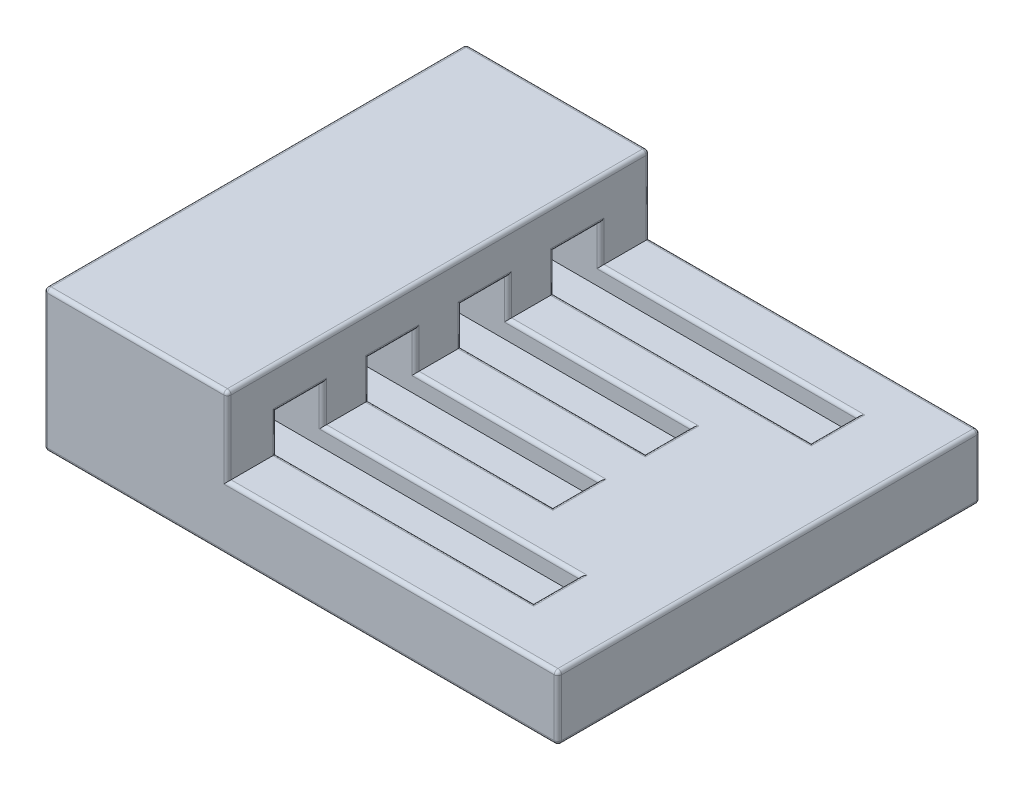
SolidWorks part; units mm, degrees
material "Ceramic Porcelain"
ref_plane "Front Plane" through (0, 0, 0) normal (0, 0, 1) x (1, 0, 0)
ref_plane "Top Plane" through (0, 0, 0) normal (0, 1, 0) x (1, 0, 0)
ref_plane "Right Plane" through (0, 0, 0) normal (1, 0, 0) x (0, 0, -1)
sketch "Sketch1" plane through (0, 0, 0) normal (0, 0, 1) x (1, 0, 0)
  line L0 (5, 3.85) -> (5, 1.75)
  line L1 (0, 0) -> (5, 0)
  line L2 (0, 0) -> (0, 3.85)
  line L3 (0, 3.85) -> (5, 3.85)
  line L4 (5, 0) -> (5, 3.85) construction
  line L5 (5, 0) -> (14, 0)
  line L6 (5, 0) -> (5, 1.75) construction
  line L7 (5, 1.75) -> (14, 1.75)
  line L8 (14, 0) -> (14, 1.75)
  dimension "D1" = 5
  dimension "D2" = 3.85
  dimension "D3" = 9
  dimension "D4" = 1.75
extrude "Boss-Extrude1" add sketch "Sketch1" along normal mid plane 11.5
sketch "Sketch2" plane through (0, 1.75, 0) normal (0, 1, 0) x (1, 0, 0)
  line L0 (0, -5.75) -> (0, 5.75) construction
  line L1 (0, 4.41) -> (12, 4.41)
  line L2 (0, 4.41) -> (0, 3.15)
  line L3 (0, 3.15) -> (12, 3.15)
  line L4 (12, 4.41) -> (12, 3.15)
  line L5 (14, -5.75) -> (14, 5.75) construction
  line L6 (0, 0) -> (14, 0) construction
  line L7 (0, 1.89) -> (10, 1.89)
  line L8 (0, 1.89) -> (0, 0.63)
  line L9 (0, 0.63) -> (10, 0.63)
  line L10 (10, 1.89) -> (10, 0.63)
  line L11 (10, -1.89) -> (10, -0.63)
  line L12 (0, -0.63) -> (10, -0.63)
  line L13 (0, -1.89) -> (0, -0.63)
  line L14 (0, -1.89) -> (10, -1.89)
  line L15 (12, -4.41) -> (12, -3.15)
  line L16 (0, -3.15) -> (12, -3.15)
  line L17 (0, -4.41) -> (0, -3.15)
  line L18 (0, -4.41) -> (12, -4.41)
  dimension "D1" = 4
  dimension "D2" = 2
  dimension "D3" = 1.26
  dimension "D4" = 1.26
  dimension "D5" = 0.63
extrude "Cut-Extrude1" cut sketch "Sketch2" against normal blind 0.5 and the other way blind 1
fillet "Fillet1" radius 0.1 57 edges at (14, 0.875, 5.75) (0, 1.25, 3.78) (0, 2.75, 3.78) (0, 2, 4.41) (0, 2, 3.15) (0, 1.25, 1.26) (0, 2.75, 1.26) (0, 2, 1.89) (0, 2, 0.63) (0, 1.25, -1.26) (0, 2.75, -1.26) (0, 2, -1.89) (0, 2, -0.63) (0, 1.25, -3.78) (0, 2.75, -3.78) (0, 2, -4.41) (0, 2, -3.15) (8.5, 1.75, 3.15) (8.5, 1.75, 4.41) (7.5, 1.75, 0.63) (7.5, 1.75, 1.89) (7.5, 1.75, -1.89) (7.5, 1.75, -0.63) (8.5, 1.75, -4.41) (8.5, 1.75, -3.15) (0, 1.925, -5.75) (7, 0, -5.75) (9.5, 1.75, -5.75) (5, 2.8, -5.75) (2.5, 3.85, -5.75) (0, 1.925, 5.75) (7, 0, 5.75) (9.5, 1.75, 5.75) (5, 2.8, 5.75) (2.5, 3.85, 5.75) (0, 3.85, 0) (5, 3.85, 0) (14, 1.75, 0) (14, 0, 0) (0, 0, 0) (5, 2.75, 3.78) (5, 2.25, 3.15) (5, 2.25, 4.41) (5, 2.75, 1.26) (5, 2.25, 0.63) (5, 2.25, 1.89) (5, 2.75, -1.26) (5, 2.25, -1.89) (5, 2.25, -0.63) (5, 2.75, -3.78) (5, 2.25, -4.41) (5, 2.25, -3.15) (12, 1.75, 3.78) (10, 1.75, 1.26) (10, 1.75, -1.26) (12, 1.75, -3.78) (14, 0.875, -5.75)
